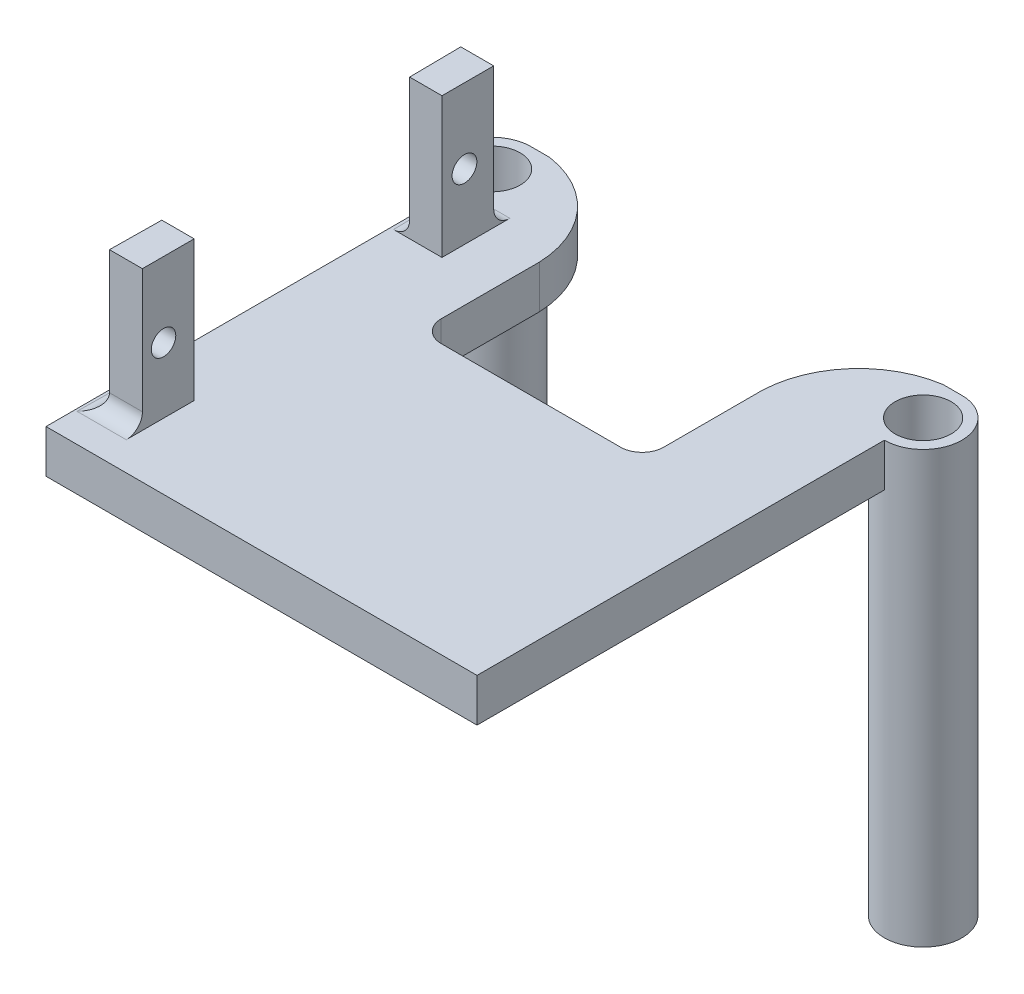
SolidWorks part; units mm, degrees
ref_plane "Front Plane" through (0, 0, 0) normal (0, 0, 1) x (1, 0, 0)
ref_plane "Top Plane" through (0, 0, 0) normal (0, 1, 0) x (1, 0, 0)
ref_plane "Right Plane" through (0, 0, 0) normal (1, 0, 0) x (0, 0, -1)
sketch "Sketch1" plane through (0, 0, 0) normal (0, 1, 0) x (1, 0, 0)
  circle A2 centre (-16.3341, 4.404) radius 2.6
  circle A3 centre (-16.3341, 4.404) radius 3.6
  circle A4 centre (23.6659, 4.404) radius 2.6
  circle A5 centre (23.6659, 4.404) radius 3.6
  dimension "D2" = 5.2
  dimension "D1" = 7.2
  dimension "D3" = 40
extrude "Boss-Extrude1" add sketch "Sketch1" along normal blind 40
sketch "Sketch2" plane through (0, 40, 0) normal (0, 1, 0) x (1, 0, 0)
  line L6 (-16.3341, 8.004) -> (23.6659, 8.004)
  line L9 (-16.3341, 0.804) -> (-16.3341, -36.996)
  line L10 (-16.3341, -36.996) -> (23.6659, -36.996)
  line L11 (23.6659, -36.996) -> (23.6659, 0.804)
  circle A0 centre (-16.3341, 4.404) radius 3.6 construction
  circle A1 centre (23.6659, 4.404) radius 3.6 construction
  arc A4 (-16.3341, 0.804) -> (-16.3341, 8.004) centre (-16.3341, 4.404) ccw
  arc A5 (23.6659, 0.804) -> (23.6659, 8.004) centre (23.6659, 4.404) cw
  dimension "D3" = 45
extrude "Boss-Extrude2" add sketch "Sketch2" against normal blind 4
sketch "Sketch4" plane through (0, 40, 0) normal (0, 1, 0) x (1, 0, 0)
  line L0 (23.6659, 8.004) -> (-16.3341, 8.004) construction
  line L1 (-6.6566, 8.004) -> (13.9884, 8.004)
  line L2 (-6.6566, 8.004) -> (-6.6566, -11.996)
  line L3 (-6.6566, -11.996) -> (13.9884, -11.996)
  line L4 (13.9884, 8.004) -> (13.9884, -11.996)
  line L5 (23.6659, -36.996) -> (23.6659, 0.804) construction
  line L6 (-16.3341, 0.804) -> (-16.3341, -36.996) construction
  dimension "D1" = 9.6775
  dimension "D2" = 9.6775
  dimension "D3" = 20
extrude "Cut-Extrude2" cut sketch "Sketch4" against normal blind 10
sketch "Sketch5" plane through (0, 40, 0) normal (0, 1, 0) x (1, 0, 0)
  line L0 (-6.6566, -0.236) -> (-11.5466, -0.236) construction
  line L1 (-6.6566, 8.004) -> (-6.6566, -11.996) construction
  line L2 (-11.5466, -0.236) -> (-11.5466, -5.036) construction
  line L3 (-6.6566, 8.004) -> (-16.3341, 8.004) construction
  line L5 (-11.5466, -5.036) -> (-14.5466, -5.036)
  line L6 (-11.5466, -5.036) -> (-11.5466, -0.236)
  line L7 (-11.5466, -0.236) -> (-14.6032, -0.236)
  line L8 (-14.5466, -5.036) -> (-14.6032, -0.236)
  line L10 (-14.5466, -28.036) -> (-11.5466, -28.036)
  line L11 (-14.5466, -28.036) -> (-14.6032, -32.836)
  line L12 (-14.6032, -32.836) -> (-11.5466, -32.836)
  line L13 (-11.5466, -28.036) -> (-11.5466, -32.836)
  dimension "D1" = 4.89
  dimension "D2" = 4.8
  dimension "D3" = 8.24
  dimension "D4" = 4.8
  dimension "D5" = 23
  dimension "D6" = 3
  dimension "D7" = 3
  dimension "D8" = 0
extrude "Boss-Extrude3" add sketch "Sketch5" along normal blind 13 contours L11 L10 L13 L12 | L6 L5 L8 L7
fillet "Fillet3" radius 1.5 4 edges at (-13.0749, 40, 32.836) (-13.0749, 40, 0.236) (-14.5749, 40, 2.636) (-14.5749, 40, 30.436)
sketch "Sketch6" plane through (-11.5466, 0.245, 0.2492) normal (1, 0, 0) x (0, 0, -1)
  line L0 (1.0532, -0.245) -> (8.2532, -0.245) construction
  circle A0 centre (-30.6265, 45.8325) radius 1.1356
  circle A1 centre (-2.6993, 45.8325) radius 1.15
  dimension "D1" = 2.3
  dimension "D2" = 46.0775
extrude "Cut-Extrude3" cut sketch "Sketch6" against normal blind 13
fillet "Fillet4" radius 2 4 edges at (-6.6566, 38, 11.996) (-6.6566, 38, -8.004) (13.9884, 38, -8.004) (13.9884, 38, 11.996)
sketch "Sketch9" plane through (0, 0, 0) normal (0, -1, 0) x (1, 0, 0)
  circle A0 centre (-16.3341, -4.404) radius 1.6
  circle A1 centre (-16.3341, -4.404) radius 2.8516
  dimension "D1" = 3.2
extrude "Boss-Extrude4" add sketch "Sketch9" against normal blind 2
sketch "Sketch10" plane through (0, 0, 0) normal (0, -1, 0) x (1, 0, 0)
  circle A0 centre (23.6659, -4.404) radius 1.6
  circle A1 centre (23.6659, -4.404) radius 2.8958
  dimension "D1" = 3.2
extrude "Boss-Extrude5" add sketch "Sketch10" against normal blind 4
sketch "Sketch11" plane through (0, 0, 36.996) normal (0, 0, 1) x (1, 0, 0)
  line L0 (-16.3341, 36) -> (23.6659, 36) construction
  line L1 (3.6659, 36) -> (65.8483, 36)
  line L3 (-8.6753, 40.02) -> (65.8483, 40.02)
  line L4 (65.8483, 36) -> (65.8483, 40.02)
  line L6 (3.6659, 36) -> (-54.1517, 36)
  line L8 (-8.6753, 40.02) -> (-54.1517, 40.02)
  line L9 (-54.1517, 36) -> (-54.1517, 40.02)
  dimension "D1" = 120
extrude "Boss-Extrude6" [suppressed] add sketch "Sketch11" along normal blind 130
sketch "Sketch12" plane through (0, 40, 0) normal (0, 1, 0) x (1, 0, 0)
  line L1 (-8.6566, 8.004) -> (-16.3341, 8.004) construction
  line L3 (-6.6566, 6.004) -> (-6.6566, -9.996) construction
  line L4 (-14.5972, 8.004) -> (-6.5262, 8.004)
  line L5 (-6.5262, 8.004) -> (-6.6566, -0.8947)
  arc A0 (-14.5972, 8.004) -> (-6.6566, -0.8947) centre (-15.9572, -1.2017) cw
extrude "Cut-Extrude4" cut sketch "Sketch12" against normal blind 10
ref_plane "Plane1" through (3.6659, 0, 0) normal (-1, 0, 0) x (0, 0, 1)
mirror "Mirror1" about plane through (3.6659, 0, 0) normal (-1, 0, 0) of "Cut-Extrude4"
